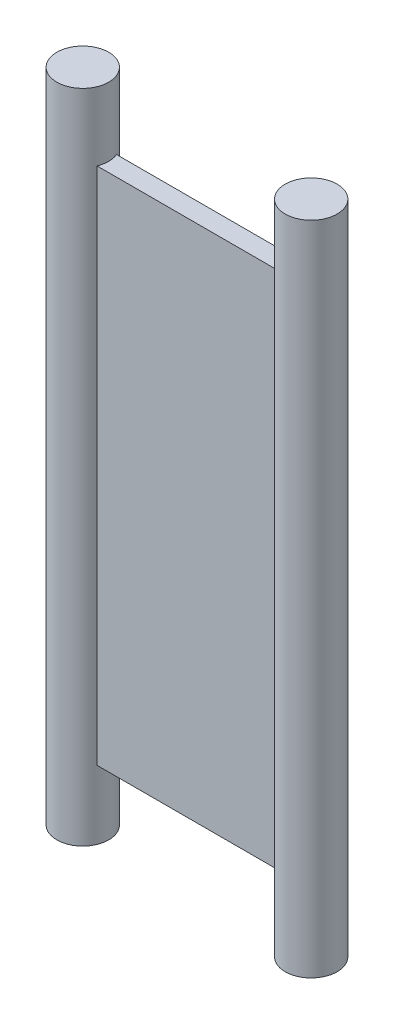
SolidWorks part; units mm, degrees
ref_plane "Front Plane" through (0, 0, 0) normal (0, 0, 1) x (1, 0, 0)
ref_plane "Top Plane" through (0, 0, 0) normal (0, 1, 0) x (1, 0, 0)
ref_plane "Right Plane" through (0, 0, 0) normal (1, 0, 0) x (0, 0, -1)
sketch "Sketch1" plane through (0, 0, 0) normal (0, 1, 0) x (1, 0, 0)
  line L1 (5.83, 0.5) -> (-5.83, 0.5)
  line L2 (5.83, 0.5) -> (5.83, -0.5)
  line L3 (5.83, -0.5) -> (-5.83, -0.5)
  line L4 (-5.83, 0.5) -> (-5.83, -0.5)
  line L5 (5.83, 0.5) -> (-5.83, -0.5) construction
  line L6 (5.83, -0.5) -> (-5.83, 0.5) construction
  point P0 (0, 0)
  dimension "D1" = 11.66
  dimension "D3" = 1
extrude "Boss-Extrude1" add sketch "Sketch1" along normal blind 26.5
ref_plane "Plane1" through (0, 13.25, 0) normal (0, 1, 0) x (1, 0, 0)
sketch "Sketch2" plane through (0, 13.25, 0) normal (0, 1, 0) x (1, 0, 0)
  line L0 (5.83, -0.5) -> (5.83, 0.5) construction
  line L1 (-5.83, 0.5) -> (-5.83, -0.5) construction
  line L2 (5.83, -0.5) -> (5.83, 0.5) construction
  line L3 (-5.83, 0.5) -> (-5.83, -0.5) construction
  circle A0 centre (-5.83, 0) radius 1.325
  circle A1 centre (5.83, 0) radius 1.325
  dimension "D1" = 2.65
extrude "Boss-Extrude2" add sketch "Sketch2" along normal mid plane 33.5
